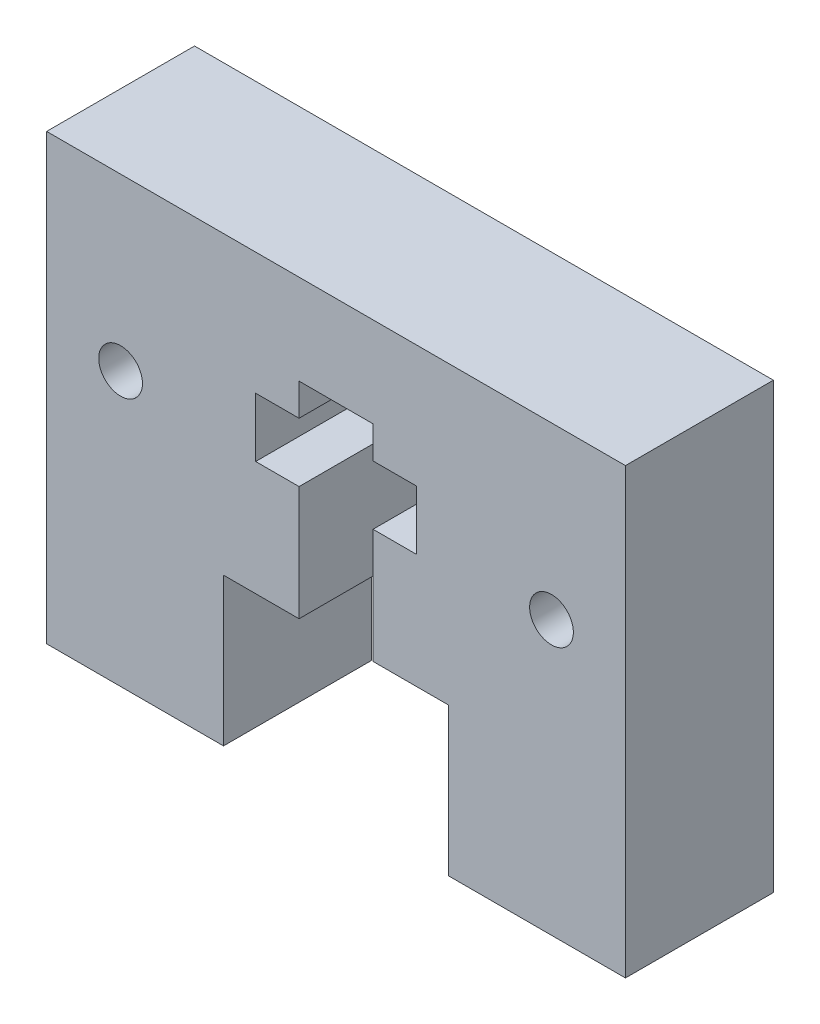
SolidWorks part; units mm, degrees
ref_plane "Front Plane" through (0, 0, 0) normal (0, 0, 1) x (1, 0, 0)
ref_plane "Top Plane" through (0, 0, 0) normal (0, 1, 0) x (1, 0, 0)
ref_plane "Right Plane" through (0, 0, 0) normal (1, 0, 0) x (0, 0, -1)
sketch "Sketch2" plane through (0, 0, 0) normal (0, 0, 1) x (1, 0, 0)
  line L0 (-42.7037, -5.842) -> (-35.7188, -5.842)
  line L1 (-35.7188, -5.842) -> (-97.3138, -5.842) construction
  line L2 (-35.7188, -5.842) -> (-35.7187, 0)
  line L3 (-35.7187, 0) -> (-26.8287, 0)
  line L4 (-26.8287, 0) -> (-26.8287, -5.842)
  line L5 (-26.8287, -5.842) -> (-19.8438, -5.842)
  line L6 (34.7663, -5.842) -> (-26.8287, -5.842) construction
  line L7 (-19.8438, -5.842) -> (-19.8438, 7.874)
  line L8 (-19.8438, 7.874) -> (-42.7037, 7.874)
  line L9 (-42.7037, 7.874) -> (-42.7037, -5.842)
  line L10 (-35.7188, -2.921) -> (-26.8287, -2.921) construction
  line L11 (-31.2738, 7.874) -> (-31.2737, 0) construction
  circle A0 centre (-39.7828, 4.953) radius 0.8636
  circle A1 centre (-22.7648, 4.953) radius 0.8636
  dimension "D5" = 1.7272
  dimension "D1" = 10.795
  dimension "D2" = 22.86
  dimension "D3" = 2.921
  dimension "D4" = 2.921
extrude "Boss-Extrude1" add sketch "Sketch2" along normal blind 5.842
sketch "Sketch3" plane through (0, 0, 5.842) normal (0, 0, 1) x (1, 0, 0)
  line L0 (-32.7343, 0) -> (-32.7343, 4.5212)
  line L1 (-32.7343, 4.5212) -> (-34.4487, 4.5212)
  line L2 (-34.4487, 4.5212) -> (-34.4487, 6.858)
  line L3 (-34.4487, 6.858) -> (-32.7343, 6.858)
  line L4 (-32.7343, 6.858) -> (-32.7342, 8.128)
  line L5 (-32.7342, 8.128) -> (-29.8133, 8.128)
  line L6 (-29.8133, 8.128) -> (-29.8132, 6.858)
  line L7 (-29.8132, 6.858) -> (-28.0987, 6.858)
  line L8 (-28.0987, 6.858) -> (-28.0987, 4.5212)
  line L9 (-28.0987, 4.5212) -> (-29.8132, 4.5212)
  line L10 (-29.8132, 4.5212) -> (-29.8132, 0)
  line L11 (-29.8132, 0) -> (-32.7343, 0)
  line L12 (-35.7187, 0) -> (-26.8287, 0) construction
  line L13 (-35.7187, -5.842) -> (-26.8288, -5.842) construction
  point P12 (-31.2737, 0)
  dimension "D1" = 2.921
  dimension "D2" = 2.3368
  dimension "D3" = 6.35
  dimension "D4" = 12.7
  dimension "D5" = 1.27
sketch "Sketch4" plane through (0, 0, 5.842) normal (0, 0, 1) x (1, 0, 0)
  line L0 (-19.8438, -5.842) -> (-19.8438, 7.874) construction
  line L1 (-42.7037, 7.874) -> (-19.8438, 7.874)
  line L2 (-42.7037, 7.874) -> (-42.7037, 11.684)
  line L3 (-42.7037, 11.684) -> (-19.8438, 11.684)
  line L4 (-19.8438, 7.874) -> (-19.8438, 11.684)
  dimension "D1" = 3.81
extrude "Boss-Extrude2" add sketch "Sketch4" against normal blind 5.842
extrude "Cut-Extrude1" cut sketch "Sketch3" against normal through all
